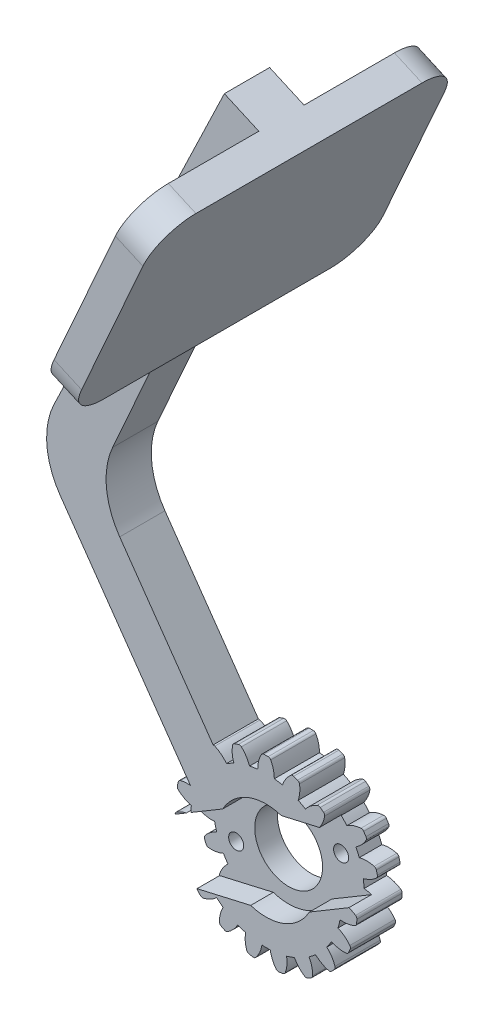
SolidWorks part; units mm, degrees
ref_plane "Front Plane" through (0, 0, 0) normal (0, 0, 1) x (1, 0, 0)
ref_plane "Top Plane" through (0, 0, 0) normal (0, 1, 0) x (1, 0, 0)
ref_plane "Right Plane" through (0, 0, 0) normal (1, 0, 0) x (0, 0, -1)
sketch "Sketch1" plane through (0, 0, 0) normal (0, 0, 1) x (1, 0, 0)
  line L0 (0, 0) -> (0, 12.075) construction
  arc A0 (-1.1, 9.9393) -> (1.1, 9.9393) centre (0, 0) ccw
  arc A1 (0.2764, 12.0718) -> (-0.2764, 12.0718) centre (0, 0) ccw
  arc A2 (0.6177, 11.8646) -> (0.2764, 12.0718) centre (0.2672, 11.6719) ccw
  arc A3 (-0.6177, 11.8646) -> (-0.2764, 12.0718) centre (-0.2672, 11.6719) cw
  arc A4 (0, 10) -> (-1.1, 9.9393) centre (0, 0) ccw construction
  arc A5 (1.1, 9.9393) -> (0, 10) centre (0, 0) ccw construction
  circle A21 centre (0, 0) radius 1.5
  spline S0 degree 3 poles (-0.6177, 11.8646) (-0.9346, 11.2883) (-1.1207, 10.6005) (-1.1, 9.9393) knots 0.104246 0.104246 0.104246 0.104246 1 1 1 1
  spline S1 degree 3 poles (0.6177, 11.8646) (0.9636, 11.2354) (1.0591, 10.6328) (1.1, 9.9393) knots 0.104246 0.104246 0.104246 0.104246 1 1 1 1
  point P127 (0, 0)
  dimension "D1" = 20
  dimension "D2" = 24.15
  dimension "D7" = 0.4
  dimension "D3" = 3
  dimension "D8" = 0.5527
  dimension "D16" = 1.2197
  dimension "D17" = 1.0456
  dimension "D4" = 1
  dimension "D5" = 1.1
  dimension "D6" = 1.2
  dimension "D9" = 0.2672
  dimension "D10" = 1.1
  dimension "D11" = 0.6177
  dimension "D12" = 1
  dimension "D13" = 1.1
  dimension "D14" = 0.6177
  dimension "D15" = 10.8
extrude "Boss-Extrude1" add sketch "Sketch1" along normal blind 6
pattern_circular "CirPattern1" count 19 over 360 about axis through (0, 0, 6) along (0, 0, -1) of "Boss-Extrude1"
sketch "Sketch2" plane through (0, 0, 6) normal (0, 0, 1) x (1, 0, 0)
  line L7 (-7.5, 0) -> (7.5, 0) construction
  line L12 (-2.5851, 3.4415) -> (-19.4151, 27.4772)
  line L13 (-20.3591, 37.2804) -> (-0.0448, 82.907)
  line L14 (-0.0448, 82.907) -> (-5.526, 85.3474)
  line L15 (-5.526, 85.3474) -> (-28.1239, 38.3511)
  line L16 (-27.3032, 28.2818) -> (-7.5, 0)
  line L17 (-7.5, 0) -> (-2.5851, 3.4415)
  arc A0 (-19.4151, 27.4772) -> (-20.3591, 37.2804) centre (-11.2236, 33.213) cw
  arc A1 (-28.1239, 38.3511) -> (-27.3032, 28.2818) centre (-19.1116, 34.0176) ccw
  point P9 (-22.6603, 32.1118)
  point P13 (0, 0)
  point P15 (-30.6603, 33.0763)
  dimension "D9" = 10
  dimension "D1" = 15
  dimension "D2" = 6
  dimension "D3" = 35
  dimension "D4" = 6
  dimension "D5" = 121
  dimension "D6" = 35
  dimension "D7" = 58
  dimension "D8" = 8
extrude "Boss-Extrude2" add sketch "Sketch2" against normal blind 6
sketch "Sketch4" plane through (0, 0, 6) normal (0, 0, 1) x (1, 0, 0)
  line L0 (5.7373, -3.0551) -> (16.8492, 3.5671)
  line L5 (14.6421, 9.0681) -> (2.0345, 6.1734)
  line L6 (-5.7373, 3.0551) -> (-16.8492, -3.5671)
  line L7 (-14.6421, -9.0681) -> (-2.0345, -6.1734)
  line L10 (5.3589, -2.6986) -> (16.5932, 3.9966)
  line L11 (14.7539, 8.5807) -> (2.0075, 5.6542)
  line L12 (-5.3589, 2.6986) -> (-16.5932, -3.9966)
  line L13 (-14.7539, -8.5807) -> (-2.0075, -5.6542)
  line L14 (5.3589, -2.6986) -> (16.5932, 3.9966) construction
  line L15 (14.7539, 8.5807) -> (2.0075, 5.6542) construction
  line L16 (-5.3589, 2.6986) -> (-16.5932, -3.9966) construction
  line L17 (-14.7539, -8.5807) -> (-2.0075, -5.6542) construction
  arc A2 (16.8492, 3.5671) -> (14.6421, 9.0681) centre (15.3134, 6.1441) ccw
  arc A3 (2.0345, 6.1734) -> (-5.7373, 3.0551) centre (0, 0) ccw
  arc A4 (-16.8492, -3.5671) -> (-14.6421, -9.0681) centre (-15.3134, -6.1441) ccw
  arc A5 (-2.0345, -6.1734) -> (5.7373, -3.0551) centre (0, 0) ccw
  arc A6 (-2.0075, -5.6542) -> (5.3589, -2.6986) centre (0, 0) ccw
  arc A7 (16.5932, 3.9966) -> (14.7539, 8.5807) centre (15.3134, 6.1441) ccw
  arc A8 (2.0075, 5.6542) -> (-5.3589, 2.6986) centre (0, 0) ccw
  arc A9 (-16.5932, -3.9966) -> (-14.7539, -8.5807) centre (-15.3134, -6.1441) ccw
  arc A10 (-2.0075, -5.6542) -> (5.3589, -2.6986) centre (0, 0) ccw construction
  arc A11 (16.5932, 3.9966) -> (14.7539, 8.5807) centre (15.3134, 6.1441) ccw construction
  arc A12 (2.0075, 5.6542) -> (-5.3589, 2.6986) centre (0, 0) ccw construction
  arc A13 (-16.5932, -3.9966) -> (-14.7539, -8.5807) centre (-15.3134, -6.1441) ccw construction
  dimension "D1" = 0.5
  dimension "D4" = 0
extrude "Cut-Extrude1" cut sketch "Sketch4" against normal blind 3
sketch "Sketch5" plane through (0, 0, 0) normal (0, 0, -1) x (-1, 0, 0)
  circle A0 centre (0, 0) radius 4.5
  dimension "D1" = 9
extrude "Cut-Extrude2" cut sketch "Sketch5" against normal through all both and the other way through all
sketch "Sketch6" plane through (0, 0, 3) normal (0, 0, 1) x (1, 0, 0)
  circle A0 centre (-6.9606, -2.7928) radius 1
  circle A1 centre (6.9606, 2.7928) radius 1
  dimension "D1" = 2
  dimension "D2" = 2
extrude "Cut-Extrude3" cut sketch "Sketch6" against normal through all both and the other way through all
sketch "Sketch7" plane through (-30.8433, 13.7323, 0) normal (0.9135, -0.4067, 0) x (0, 0, -1)
  line L0 (0, 75.7211) -> (-6, 75.7211) construction
  line L1 (-18, 45.7211) -> (12, 45.7211)
  line L2 (-23, 50.7211) -> (-23, 70.7211)
  line L3 (-18, 75.7211) -> (12, 75.7211)
  line L4 (17, 50.7211) -> (17, 70.7211)
  arc A0 (12, 75.7211) -> (17, 70.7211) centre (12, 70.7211) cw
  arc A1 (12, 45.7211) -> (17, 50.7211) centre (12, 50.7211) ccw
  arc A2 (-18, 45.7211) -> (-23, 50.7211) centre (-18, 50.7211) cw
  arc A3 (-23, 70.7211) -> (-18, 75.7211) centre (-18, 70.7211) cw
  point P6 (-3, 75.7211)
  point P7 (-3, 75.7211)
  point P10 (17, 75.7211)
  point P15 (-23, 45.7211)
  point P18 (-23, 75.7211)
  dimension "D3" = 5
  dimension "D1" = 40
  dimension "D2" = 30
extrude "Boss-Extrude3" add sketch "Sketch7" along normal blind 3 and the other way blind 1
